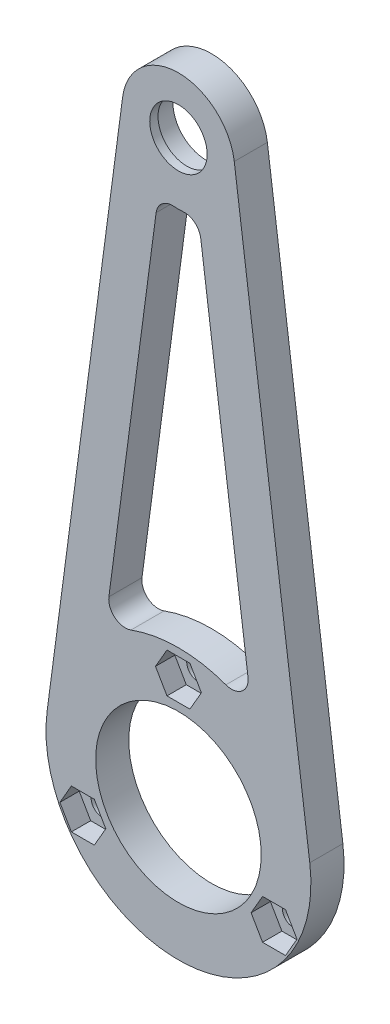
SolidWorks part; units mm, degrees
material "6061 合金"
ref_plane "前视基准面" through (0, 0, 0) normal (0, 0, 1) x (1, 0, 0)
ref_plane "上视基准面" through (0, 0, 0) normal (0, 1, 0) x (1, 0, 0)
ref_plane "右视基准面" through (0, 0, 0) normal (1, 0, 0) x (0, 0, -1)
sketch "草图1" plane through (0, 0, 0) normal (0, 0, 1) x (1, 0, 0)
  line L0 (0, 0) -> (0, 109.1958) construction
  line L1 (-23.7918, 3.1543) -> (-10.1115, 106.3406)
  line L2 (23.7918, 3.1543) -> (10.1115, 106.3406)
  line L3 (-13.3365, 21.1456) -> (-3.6242, 94.4026)
  line L4 (13.3365, 21.1456) -> (3.6242, 94.4026)
  circle A0 centre (0, 0) radius 15
  arc A1 (-23.7918, 3.1543) -> (23.7918, 3.1543) centre (0, 0) ccw
  circle A2 centre (0, 20) radius 2
  circle A3 centre (0, 105) radius 5.2
  arc A4 (10.1115, 106.3406) -> (-10.1115, 106.3406) centre (0, 105) ccw
  circle A5 centre (17.3205, -10) radius 2
  circle A6 centre (-17.3205, -10) radius 2
  arc A7 (-3.6242, 94.4026) -> (3.6242, 94.4026) centre (0, 105) ccw
  arc A8 (13.3365, 21.1456) -> (-13.3365, 21.1456) centre (0, 0) ccw
  point P17 (0, 0)
  dimension "D1" = 4
  dimension "D2" = 20
  dimension "D3" = 30
  dimension "D4" = 48
  dimension "D5" = 10.4
  dimension "D6" = 5
  dimension "D7" = 105
  dimension "D9" = 10
  dimension "D10" = 6
  dimension "D11" = 8
  dimension "D8" = 3
extrude "凸台-拉伸1" add sketch "草图1" along normal blind 6
fillet "圆角1" radius 3 4 edges at (13.3365, 21.1456, 3) (-13.3365, 21.1456, 3) (3.6242, 94.4026, 3) (-3.6242, 94.4026, 3)
sketch "草图2" plane through (0, 0, 6) normal (0, 0, 1) x (1, 0, 0)
  line L0 (0, 0) -> (-17.3205, -10) construction
  line L1 (2.0785, 16.4) -> (4.1569, 20)
  line L2 (4.1569, 20) -> (2.0785, 23.6)
  line L3 (2.0785, 23.6) -> (-2.0785, 23.6)
  line L4 (-2.0785, 23.6) -> (-4.1569, 20)
  line L5 (-4.1569, 20) -> (-2.0785, 16.4)
  line L6 (-2.0785, 16.4) -> (2.0785, 16.4)
  line L7 (19.399, -13.6) -> (21.4774, -10)
  line L8 (21.4774, -10) -> (19.399, -6.4)
  line L9 (19.399, -6.4) -> (15.242, -6.4)
  line L10 (15.242, -6.4) -> (13.1636, -10)
  line L11 (13.1636, -10) -> (15.242, -13.6)
  line L12 (15.242, -13.6) -> (19.399, -13.6)
  line L13 (-15.242, -13.6) -> (-13.1636, -10)
  line L14 (-13.1636, -10) -> (-15.242, -6.4)
  line L15 (-15.242, -6.4) -> (-19.399, -6.4)
  line L16 (-19.399, -6.4) -> (-21.4774, -10)
  line L17 (-21.4774, -10) -> (-19.399, -13.6)
  line L18 (-19.399, -13.6) -> (-15.242, -13.6)
  line L19 (17.3205, -10) -> (0, 0) construction
  circle A3 centre (0, 20) radius 3.6 construction
  circle A4 centre (17.3205, -10) radius 3.6 construction
  circle A5 centre (-17.3205, -10) radius 3.6 construction
  dimension "D1" = 7.2
extrude "切除-拉伸1" cut sketch "草图2" against normal blind 3.5
sketch "草图3" plane through (0, 0, 0) normal (0, 0, -1) x (-1, 0, 0)
  circle A0 centre (0, 105) radius 6
  dimension "D1" = 12
extrude "切除-拉伸2" cut sketch "草图3" against normal blind 4.5
sketch "草图4" plane through (0, 0, 0) normal (0, 0, -1) x (-1, 0, 0)
  circle A0 centre (0, 105) radius 7.5
  dimension "D1" = 15
extrude "切除-拉伸3" cut sketch "草图4" against normal blind 1
